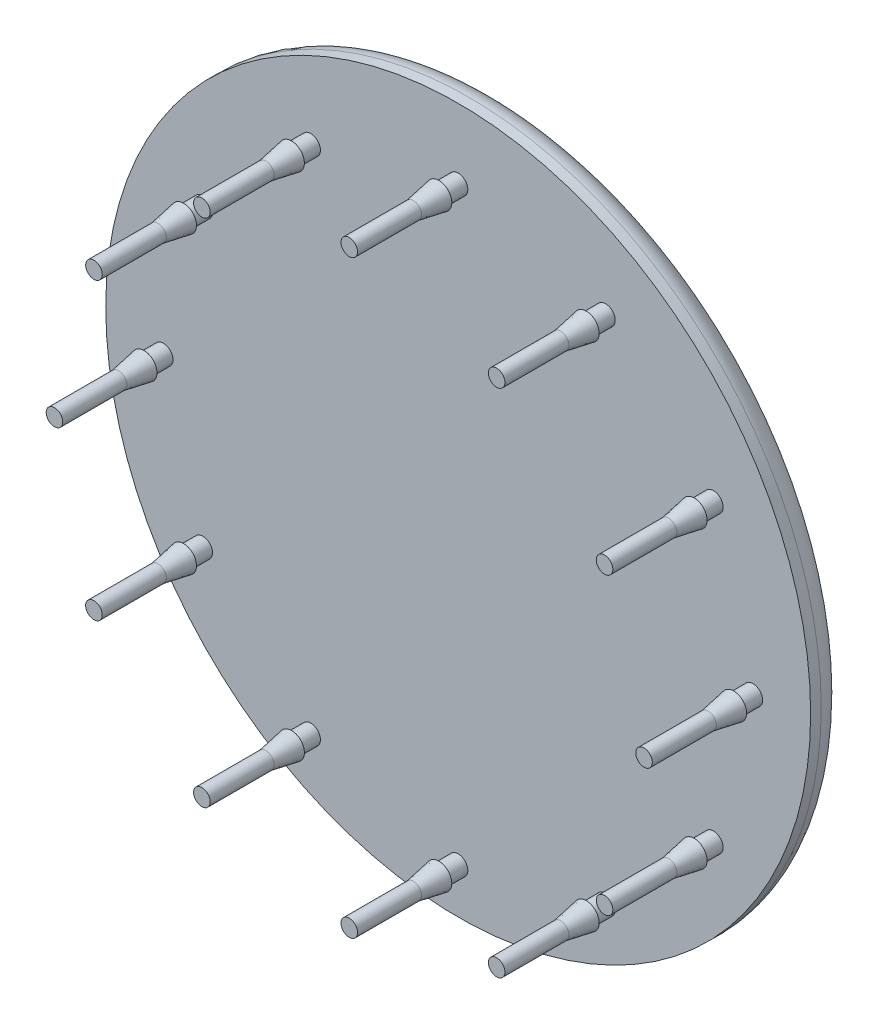
SolidWorks part; units mm, degrees
material "EPDM 60 硬度计"
ref_plane "前视基准面" through (0, 0, 0) normal (0, 0, 1) x (1, 0, 0)
ref_plane "上视基准面" through (0, 0, 0) normal (0, 1, 0) x (1, 0, 0)
ref_plane "右视基准面" through (0, 0, 0) normal (1, 0, 0) x (0, 0, -1)
sketch "草图1" plane through (0, 0, 0) normal (0, 0, 1) x (1, 0, 0)
  line L0 (0, 0) -> (0, 43.3258) construction
  line L1 (0, 43.3258) -> (0, 0) construction
  line L2 (0, 0) -> (24.2809, 0) construction
  line L3 (0, 1.93) -> (23.0151, 1.93) construction
  circle A0 centre (0, 0) radius 48.5
  circle A1 centre (0, 1.93) radius 55
  dimension "D1" = 97
  dimension "D3" = 110
  dimension "D2" = 1.93
extrude "凸台-拉伸1" add sketch "草图1" against normal blind 1
sketch "草图3" plane through (0, 0, 0) normal (1, 0, 0) x (0, 0, -1)
  line L0 (1, -53.07) -> (1, 56.93) construction
  line L1 (1, 1.93) -> (1, 56.93)
  line L2 (1, 1.93) -> (11, 1.93)
  line L3 (1, 56.93) -> (6, 56.93)
  line L4 (6, 56.93) -> (6, 1.93) construction
  arc A0 (11, 1.93) -> (6, 56.93) centre (-294, 1.93) ccw
  dimension "D1" = 10
  dimension "D2" = 5
revolve "旋转2" add sketch "草图3" angle 360 about L2
sketch "草图4" plane through (0, 0, -1) normal (0, 0, 1) x (1, 0, 0)
  line L0 (0, 0) -> (0, -46) construction
  circle A0 centre (0, 0) radius 46 construction
  circle A1 centre (0, -46) radius 1.5
  dimension "D1" = 92
  dimension "D2" = 3
extrude "凸台-拉伸2" add sketch "草图4" along normal blind 3
sketch "草图5" plane through (0, 0, 2) normal (0, 0, 1) x (1, 0, 0)
  circle A0 centre (0, -46) radius 2
  dimension "D1" = 4
extrude "凸台-拉伸3" add sketch "草图5" along normal blind 4 draft 10
sketch "草图6" plane through (0, 0, 6) normal (0, 0, 1) x (1, 0, 0)
  circle A1 centre (0, -46) radius 1.2947
  circle A2 centre (0, -46) radius 1.2947
  dimension "D1" = 0
extrude "凸台-拉伸4" add sketch "草图6" along normal blind 10
pattern_circular "阵列(圆周)1" count 12 over 360 about axis through (0, 0, 0) along (0, 0, 1) of "凸台-拉伸3", "凸台-拉伸2", "凸台-拉伸4"
sketch "草图7" plane through (0, 0, 0) normal (0, 0, 1) x (1, 0, 0)
  circle A0 centre (0, 0) radius 48.5 construction
  circle A1 centre (0, 1.93) radius 55
  circle A2 centre (0, 1.93) radius 55
  circle A3 centre (0, 0) radius 48.5
  dimension "D1" = 0
extrude "切除-拉伸1" cut sketch "草图7" against normal blind 1
fillet "圆角1" radius 4 1 edges at (55, 1.93, -6)
